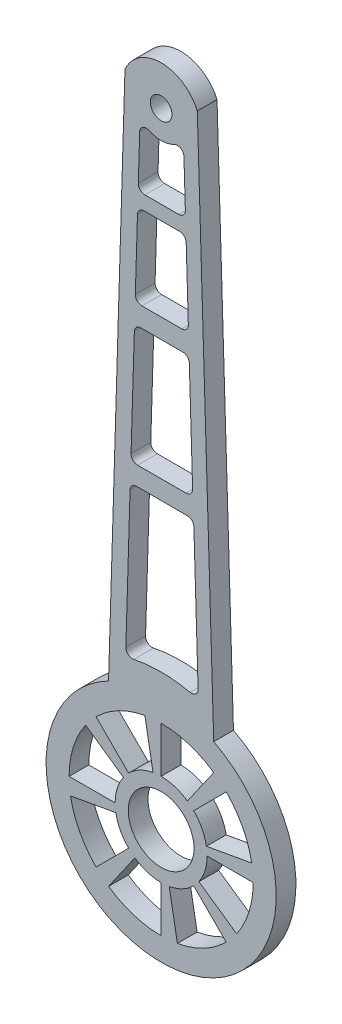
SolidWorks part; units mm, degrees
material "Thornel Mat VMA"
ref_plane "前视基准面" through (0, 0, 0) normal (0, 0, 1) x (1, 0, 0)
ref_plane "上视基准面" through (0, 0, 0) normal (0, 1, 0) x (1, 0, 0)
ref_plane "右视基准面" through (0, 0, 0) normal (1, 0, 0) x (0, 0, -1)
other "Configuration Table"
sketch "草图1" plane through (0, 0, 0) normal (0, 0, 1) x (1, 0, 0)
  line L0 (-5.5, 2.3979) -> (-8, -79.4356)
  line L1 (5.5, 2.3979) -> (8, -79.4356)
  line L2 (0, 0) -> (0, -60.2528) construction
  line L3 (-3.2033, -2.8025) -> (-3.504, -12.6454)
  line L4 (-3.504, -12.6454) -> (3.7137, -12.6454)
  line L5 (3.7137, -12.6454) -> (3.4054, -2.5531)
  line L6 (-3.5703, -14.8137) -> (-3.9576, -27.4933)
  line L7 (3.7799, -14.8137) -> (4.1673, -27.4933)
  line L8 (0, -63.95) -> (0, -95) construction
  line L9 (-3.5703, -14.8137) -> (3.7799, -14.8137)
  line L10 (-3.9576, -27.4933) -> (4.1673, -27.4933)
  line L11 (-4.0485, -30.4686) -> (4.2582, -30.4686)
  line L12 (-4.6085, -48.8002) -> (4.8182, -48.8002)
  line L13 (-4.6963, -51.6733) -> (-5.4082, -74.975)
  line L14 (-4.0485, -30.4686) -> (-4.6085, -48.8002)
  line L15 (4.2582, -30.4686) -> (4.8182, -48.8002)
  line L16 (4.9497, -51.6733) -> (5.6638, -75.0458)
  line L17 (-4.6963, -51.6733) -> (4.9497, -51.6733)
  line L18 (10.6066, -84.3934) -> (0, -95) construction
  line L19 (0, -81) -> (0, -88)
  line L20 (8, -83.5109) -> (4, -89.2554)
  line L21 (9.8995, -85.1005) -> (4.9497, -90.0503)
  line L22 (13.7809, -92.5328) -> (6.8904, -93.7664)
  line L23 (14, -95) -> (7, -95)
  line L24 (11.4891, -103) -> (5.7446, -99)
  line L25 (9.8995, -104.8995) -> (4.9497, -99.9497)
  line L26 (2.4672, -108.7809) -> (1.2336, -101.8904)
  line L27 (0, -109) -> (0, -102)
  line L28 (-8, -106.4891) -> (-4, -100.7446)
  line L29 (-9.8995, -104.8995) -> (-4.9497, -99.9497)
  line L30 (-13.7809, -97.4672) -> (-6.8904, -96.2336)
  line L31 (-14, -95) -> (-7, -95)
  line L32 (-11.4891, -87) -> (-5.7446, -91)
  line L33 (-9.8995, -85.1005) -> (-4.9497, -90.0503)
  line L34 (-2.4672, -81.2191) -> (-1.2336, -88.1096)
  arc A0 (5.5, 2.3979) -> (-5.5, 2.3979) centre (0, 0) ccw
  arc A1 (-8, -79.4356) -> (8, -79.4356) centre (0, -95) ccw
  circle A2 centre (0, 0) radius 1.65
  circle A9 centre (0, -95) radius 5
  arc A10 (-3.2033, -2.8025) -> (3.4054, -2.5531) centre (0, 0) ccw
  arc A12 (5.6638, -75.0458) -> (-5.4082, -74.975) centre (0, -95) ccw
  arc A18 (-5.7446, -91) -> (-7, -95) centre (0, -95) ccw
  arc A19 (-11.4891, -87) -> (-14, -95) centre (0, -95) ccw
  arc A20 (-1.2336, -88.1096) -> (-4.9497, -90.0503) centre (0, -95) ccw
  arc A21 (-2.4672, -81.2191) -> (-9.8995, -85.1005) centre (0, -95) ccw
  arc A22 (8, -83.5109) -> (0, -81) centre (0, -95) ccw
  arc A23 (4, -89.2554) -> (0, -88) centre (0, -95) ccw
  arc A24 (6.8904, -93.7664) -> (4.9497, -90.0503) centre (0, -95) ccw
  arc A25 (13.7809, -92.5328) -> (9.8995, -85.1005) centre (0, -95) ccw
  arc A26 (5.7446, -99) -> (7, -95) centre (0, -95) ccw
  arc A27 (-4, -100.7446) -> (0, -102) centre (0, -95) ccw
  arc A28 (-8, -106.4891) -> (0, -109) centre (0, -95) ccw
  arc A29 (-13.7809, -97.4672) -> (-9.8995, -104.8995) centre (0, -95) ccw
  arc A30 (1.2336, -101.8904) -> (4.9497, -99.9497) centre (0, -95) ccw
  arc A31 (-6.8904, -96.2336) -> (-4.9497, -99.9497) centre (0, -95) ccw
  arc A32 (2.4672, -108.7809) -> (9.8995, -104.8995) centre (0, -95) ccw
  arc A33 (11.4891, -103) -> (14, -95) centre (0, -95) ccw
  point P4 (5.7446, -75)
  point P9 (4.9497, -51.6733)
  point P14 (4.9497, -48.8002)
  point P15 (4.1985, -29.6487)
  point P16 (4.1965, -27.4933)
  point P49 (0, -95)
  point P66 (0, -75)
  point P67 (3.7715, -12.6454)
  point P68 (4.1673, -30.4686)
  dimension "D1" = 12
  dimension "D2" = 35
  dimension "D5" = 3.3
  dimension "D4" = 10
  dimension "D3" = 95
  dimension "D9" = 16
  dimension "D10" = 11
  dimension "D13" = 45
extrude "凸台-拉伸1" add sketch "草图1" along normal blind 3
fillet "圆角1" radius 1 16 edges at (3.4054, -2.5531, 1.5) (-3.2033, -2.8025, 1.5) (3.7137, -12.6454, 1.5) (-3.504, -12.6454, 1.5) (3.7799, -14.8137, 1.5) (-3.5703, -14.8137, 1.5) (-3.9576, -27.4933, 1.5) (4.1673, -27.4933, 1.5) (-4.0485, -30.4686, 1.5) (4.2582, -30.4686, 1.5) (-4.6085, -48.8002, 1.5) (4.8182, -48.8002, 1.5) (4.9497, -51.6733, 1.5) (-4.6963, -51.6733, 1.5) (-5.4082, -74.975, 1.5) (5.6638, -75.0458, 1.5)
